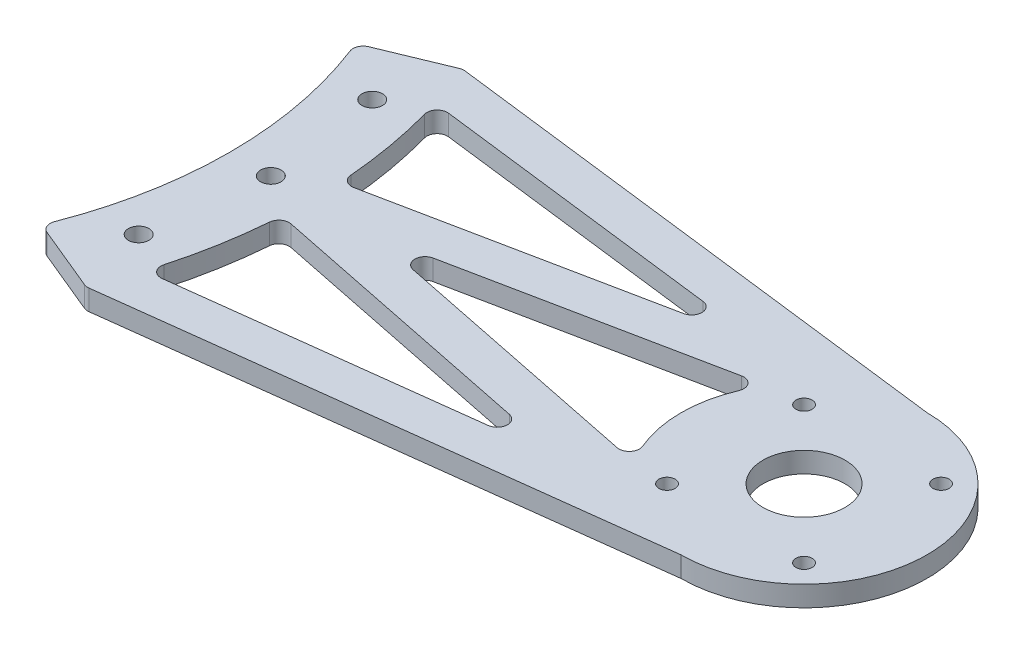
SolidWorks part; units mm, degrees
material "Teak"
ref_plane "Front Plane" through (0, 0, 0) normal (0, 0, 1) x (1, 0, 0)
ref_plane "Top Plane" through (0, 0, 0) normal (0, 1, 0) x (1, 0, 0)
ref_plane "Right Plane" through (0, 0, 0) normal (1, 0, 0) x (0, 0, -1)
sketch "Sketch2" plane through (0, 0, 0) normal (0, 1, 0) x (1, 0, 0)
  line L0 (0.9649, -29.1093) -> (82.4552, -19.0617)
  line L1 (82.4552, 19.0617) -> (0.9649, 29.1093)
  line L2 (-9.7349, -24.9005) -> (0.1631, -29.0004)
  line L3 (0.1631, 29.0004) -> (-9.7349, 24.9005)
  line L4 (50.294, 16.629) -> (5.3561, 22.1698)
  line L5 (7.9885, 4.8654) -> (50.4163, 13.4978)
  line L6 (5.3561, -22.1698) -> (50.294, -16.629)
  line L7 (50.4163, -13.4978) -> (7.9885, -4.8654)
  line L8 (63.2397, 9.6268) -> (23.5705, 1.5556)
  line L9 (23.5705, -1.5556) -> (63.2397, -9.6268)
  arc A0 (82.6418, -19.0498) -> (82.6418, 19.0498) centre (82.55, 0) ccw
  arc A1 (0.1631, -29.0004) -> (0.9649, -29.1093) centre (0.7706, -27.5337) ccw
  arc A2 (-10.6084, -22.8623) -> (-10.6084, 22.8623) centre (-69.85, 0) ccw
  arc A3 (-10.6084, -22.8623) -> (-9.7349, -24.9005) centre (-9.1274, -23.4338) ccw
  arc A4 (-9.7349, 24.9005) -> (-10.6084, 22.8623) centre (-9.1274, 23.4338) ccw
  arc A5 (0.9649, 29.1093) -> (0.1631, 29.0004) centre (0.7706, 27.5337) ccw
  arc A6 (82.4552, 19.0617) -> (82.6418, 19.0498) centre (82.6494, 20.6373) ccw
  arc A7 (82.6418, -19.0498) -> (82.4552, -19.0617) centre (82.6494, -20.6373) ccw
  arc A8 (6.0899, 6.29) -> (3.631, 20.1739) centre (-69.85, 0) ccw
  arc A9 (5.3561, 22.1698) -> (3.631, 20.1739) centre (5.1618, 20.5942) ccw
  arc A10 (50.4163, 13.4978) -> (50.294, 16.629) centre (50.0998, 15.0534) ccw
  arc A11 (6.0899, 6.29) -> (7.9885, 4.8654) centre (7.672, 6.421) ccw
  arc A12 (3.631, -20.1739) -> (5.3561, -22.1698) centre (5.1618, -20.5942) ccw
  arc A13 (3.631, -20.1739) -> (6.0899, -6.29) centre (-69.85, 0) ccw
  arc A14 (7.9885, -4.8654) -> (6.0899, -6.29) centre (7.672, -6.421) ccw
  arc A15 (50.294, -16.629) -> (50.4163, -13.4978) centre (50.0998, -15.0534) ccw
  arc A16 (65.0173, 7.4503) -> (63.2397, 9.6268) centre (63.5562, 8.0712) ccw
  arc A17 (65.0173, 7.4503) -> (65.0173, -7.4503) centre (82.55, 0) ccw
  arc A18 (63.2397, -9.6268) -> (65.0173, -7.4503) centre (63.5562, -8.0712) ccw
  arc A19 (23.5705, 1.5556) -> (23.5705, -1.5556) centre (23.887, 0) ccw
  circle A20 centre (-2.3801, 18.0785) radius 1.5875
  circle A21 centre (71.9434, -10.6066) radius 1.25
  circle A22 centre (93.1566, 10.6066) radius 1.25
  circle A23 centre (0, 0) radius 1.5875
  circle A24 centre (82.55, 0) radius 6.35
  circle A25 centre (-2.3801, -18.0785) radius 1.5875
  circle A26 centre (93.1566, -10.6066) radius 1.25
  circle A27 centre (71.9434, 10.6066) radius 1.25
extrude "Boss-Extrude1" add sketch "Sketch2" along normal blind 3.175
